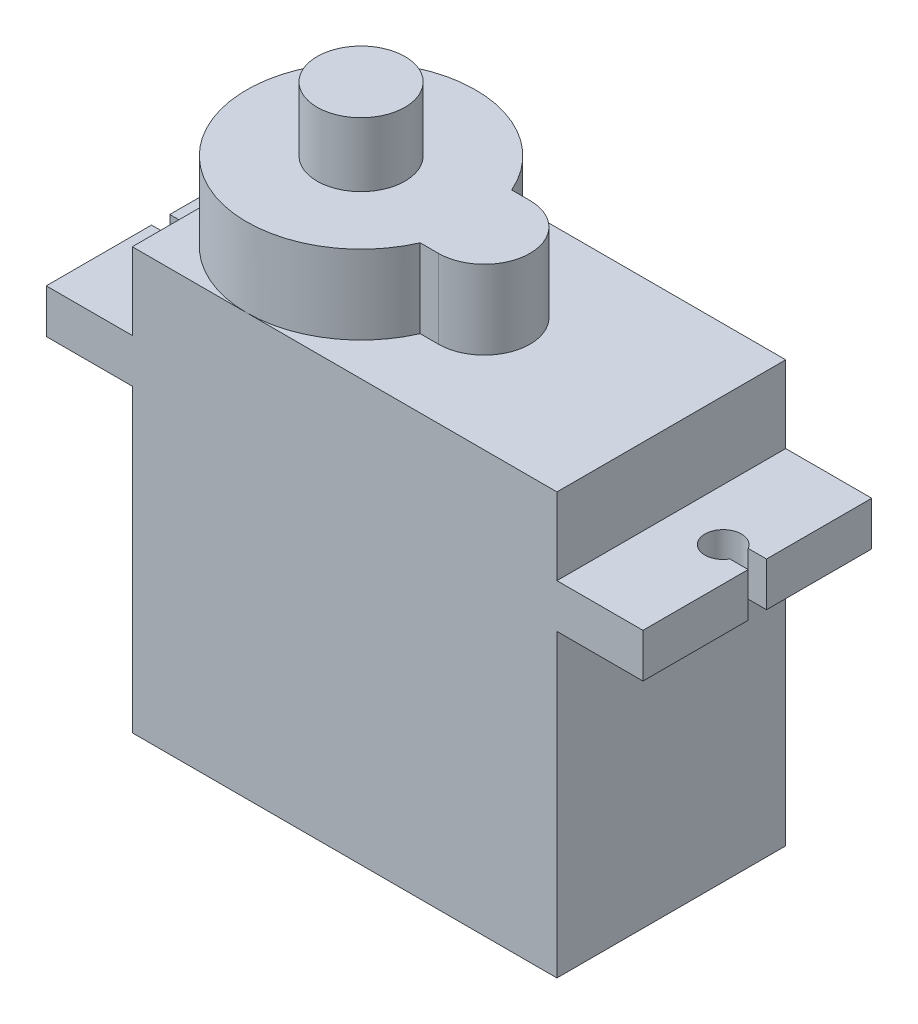
SolidWorks part; units mm, degrees
ref_plane "Front Plane" through (0, 0, 0) normal (0, 0, 1) x (1, 0, 0)
ref_plane "Top Plane" through (0, 0, 0) normal (0, 1, 0) x (1, 0, 0)
ref_plane "Right Plane" through (0, 0, 0) normal (1, 0, 0) x (0, 0, -1)
sketch "Sketch1" plane through (0, 0, 0) normal (0, 0, 1) x (1, 0, 0)
  line L0 (0, 0) -> (23.2, 0)
  line L1 (23.2, 0) -> (23.2, 16.4)
  line L2 (23.2, 16.4) -> (27.9, 16.4)
  line L3 (27.9, 16.4) -> (27.9, 18.8)
  line L4 (27.9, 18.8) -> (23.2, 18.8)
  line L5 (-4.7, 18.8) -> (-4.7, 16.4)
  line L6 (-4.7, 16.4) -> (0, 16.4)
  line L7 (0, 16.4) -> (0, 0)
  line L8 (0, 18.8) -> (0, 23)
  line L9 (0, 23) -> (23.2, 23)
  line L10 (23.2, 23) -> (23.2, 18.8)
  line L11 (0, 18.8) -> (-4.7, 18.8)
  dimension "D1" = 23.2
  dimension "D2" = 16.4
  dimension "D3" = 32.6
  dimension "D4" = 2.4
  dimension "D5" = 23
extrude "Boss-Extrude1" add sketch "Sketch1" along normal blind 12.5
sketch "Sketch2" plane through (0, 18.8, 0) normal (0, 1, 0) x (1, 0, 0)
  line L0 (11.6, -12.5) -> (11.6, 0) construction
  line L1 (23.2, -12.5) -> (0, -12.5) construction
  line L2 (23.2, 0) -> (0, 0) construction
  line L3 (27.9, -6.75) -> (27.9, -5.75)
  line L4 (-4.7, -6.75) -> (-3.7, -6.75)
  line L5 (-4.7, -12.5) -> (-4.7, 0) construction
  line L6 (-4.7, -5.75) -> (-3.7, -5.75)
  line L7 (-4.7, -6.75) -> (-4.7, -5.75)
  line L8 (27.9, -5.75) -> (26.9, -5.75)
  line L9 (27.9, -6.75) -> (26.9, -6.75)
  arc A0 (-3.7, -6.75) -> (-3.7, -5.75) centre (-2.834, -6.25) ccw
  arc A1 (26.9, -6.75) -> (26.9, -5.75) centre (26.034, -6.25) cw
  point P10 (11.6, -6.25)
  point P15 (0, 0)
  point P18 (-4.7, -6.25)
  point P21 (27.9, -6.25)
  dimension "D1" = 2
  dimension "D2" = 1
  dimension "D3" = 1
sketch "Sketch3" plane through (0, 23, 0) normal (0, 1, 0) x (1, 0, 0)
  line L0 (0, -12.5) -> (0, 0) construction
  line L1 (23.2, -12.5) -> (0, -12.5) construction
  line L7 (11.9782, -8.75) -> (12.9782, -8.75)
  line L9 (11.9782, -3.75) -> (12.9782, -3.75)
  arc A0 (11.9782, -3.75) -> (11.9782, -8.75) centre (6.25, -6.25) ccw
  arc A1 (12.9782, -8.75) -> (12.9782, -3.75) centre (12.9782, -6.25) ccw
  point P1 (12.3127, -7.7688)
  point P2 (0, 0)
  dimension "D1" = 5
  dimension "D2" = 1
extrude "Boss-Extrude2" add sketch "Sketch3" along normal blind 4.3
sketch "Sketch4" plane through (0, 27.3, 0) normal (0, 1, 0) x (1, 0, 0)
  circle A0 centre (6.25, -6.25) radius 2.4
  arc A1 (11.9782, -3.75) -> (11.9782, -8.75) centre (6.25, -6.25) ccw construction
  dimension "D1" = 4.8
extrude "Boss-Extrude3" add sketch "Sketch4" along normal blind 3.5
extrude "Cut-Extrude1" cut sketch "Sketch2" against normal up to next
